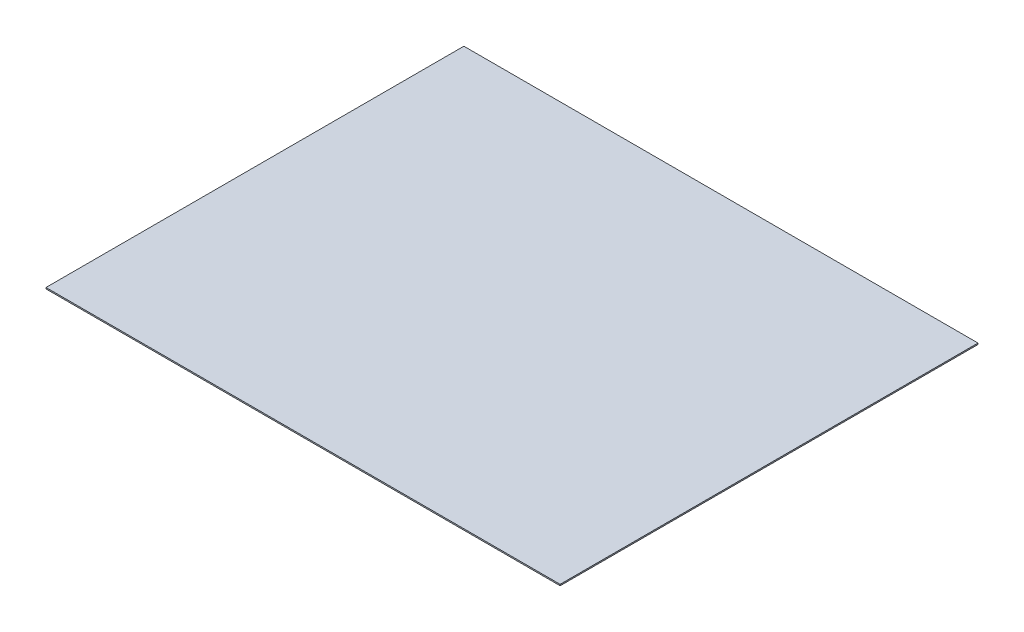
SolidWorks part; units mm, degrees
ref_plane "Front Plane" through (0, 0, 0) normal (0, 0, 1) x (1, 0, 0)
ref_plane "Top Plane" through (0, 0, 0) normal (0, 1, 0) x (1, 0, 0)
ref_plane "Right Plane" through (0, 0, 0) normal (1, 0, 0) x (0, 0, -1)
sketch "Sketch1" plane through (0, 0, 0) normal (0, 1, 0) x (1, 0, 0)
  line L1 (0, 0) -> (625.602, 0)
  line L2 (0, 0) -> (0, 508.4623)
  line L3 (0, 508.4623) -> (625.602, 508.4623)
  line L4 (625.602, 0) -> (625.602, 508.4623)
  dimension "D1" = 508.4623
  dimension "D2" = 625.602
extrude "Boss-Extrude1" add sketch "Sketch1" along normal blind 1.5875
